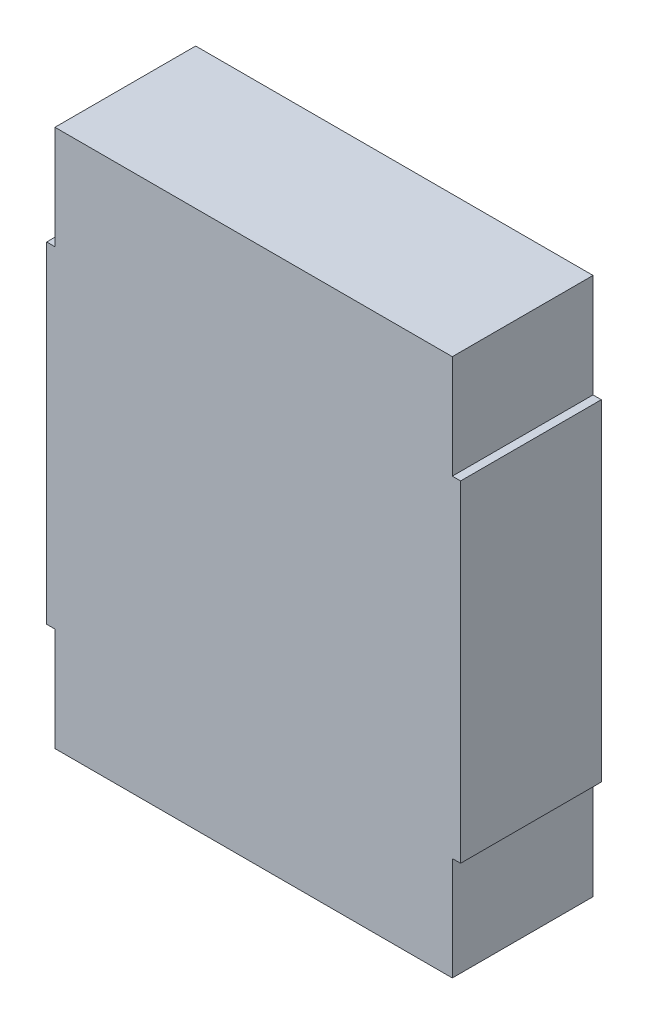
SolidWorks part; units mm, degrees
ref_plane "前视基准面" through (0, 0, 0) normal (0, 0, 1) x (1, 0, 0)
ref_plane "上视基准面" through (0, 0, 0) normal (0, 1, 0) x (1, 0, 0)
ref_plane "右视基准面" through (0, 0, 0) normal (1, 0, 0) x (0, 0, -1)
sketch "草图1" plane through (0, 0, 0) normal (0, 0, 1) x (1, 0, 0)
  line L0 (-2.4, -3.25) -> (-2.4, -2)
  line L1 (-2.4, -2) -> (-2.5, -2)
  line L2 (-2.5, -2) -> (-2.5, 2)
  line L3 (-2.5, 2) -> (-2.4, 2)
  line L4 (-2.4, 2) -> (-2.4, 3.25)
  line L5 (-2.4, 3.25) -> (2.4, 3.25)
  line L6 (2.4, 3.25) -> (2.4, 2)
  line L7 (2.4, 2) -> (2.5, 2)
  line L8 (2.5, 2) -> (2.5, -2)
  line L9 (2.5, -2) -> (2.4, -2)
  line L10 (2.4, -2) -> (2.4, -3.25)
  line L11 (2.4, -3.25) -> (-2.4, -3.25)
extrude "Component_Outline" add sketch "草图1" along normal blind 1.7 separate body
sketch3d "3D草图1"
  line L0 (0, 0, 0) -> (1, 0, 0)
  line L1 (0, 0, 0) -> (0, 1, 0)
  line L2 (0, 0, 0) -> (0, 0, 1)
  point P0 (0, 0, 0)
